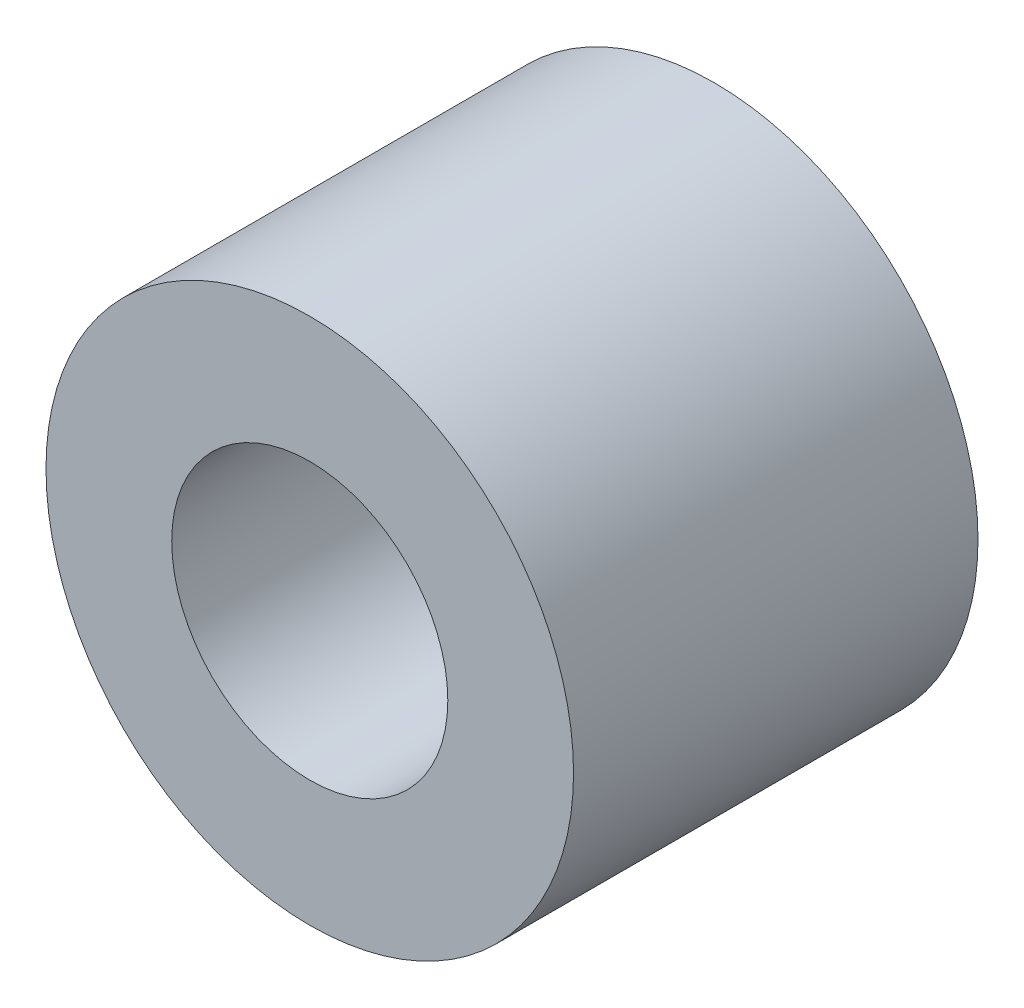
SolidWorks part; units mm, degrees
ref_plane "Alzado" through (0, 0, 0) normal (0, 0, 1) x (1, 0, 0)
ref_plane "Planta" through (0, 0, 0) normal (0, 1, 0) x (1, 0, 0)
ref_plane "Vista lateral" through (0, 0, 0) normal (1, 0, 0) x (0, 0, -1)
sketch "Croquis1" plane through (0, 0, 0) normal (0, 0, 1) x (1, 0, 0)
  circle A0 centre (0, 0) radius 15
extrude "Saliente-Extruir1" add sketch "Croquis1" against normal blind 23
sketch "Croquis2" plane through (0, 0, 0) normal (0, 0, 1) x (1, 0, 0)
  circle A0 centre (0, 0) radius 7.85
extrude "Cortar-Extruir1" cut sketch "Croquis2" against normal blind 16
sketch "Croquis3" plane through (0, 0, -23) normal (0, 0, -1) x (-1, 0, 0)
  circle A0 centre (0, 0) radius 1.5
extrude "Cortar-Extruir2" cut sketch "Croquis3" against normal blind 16
